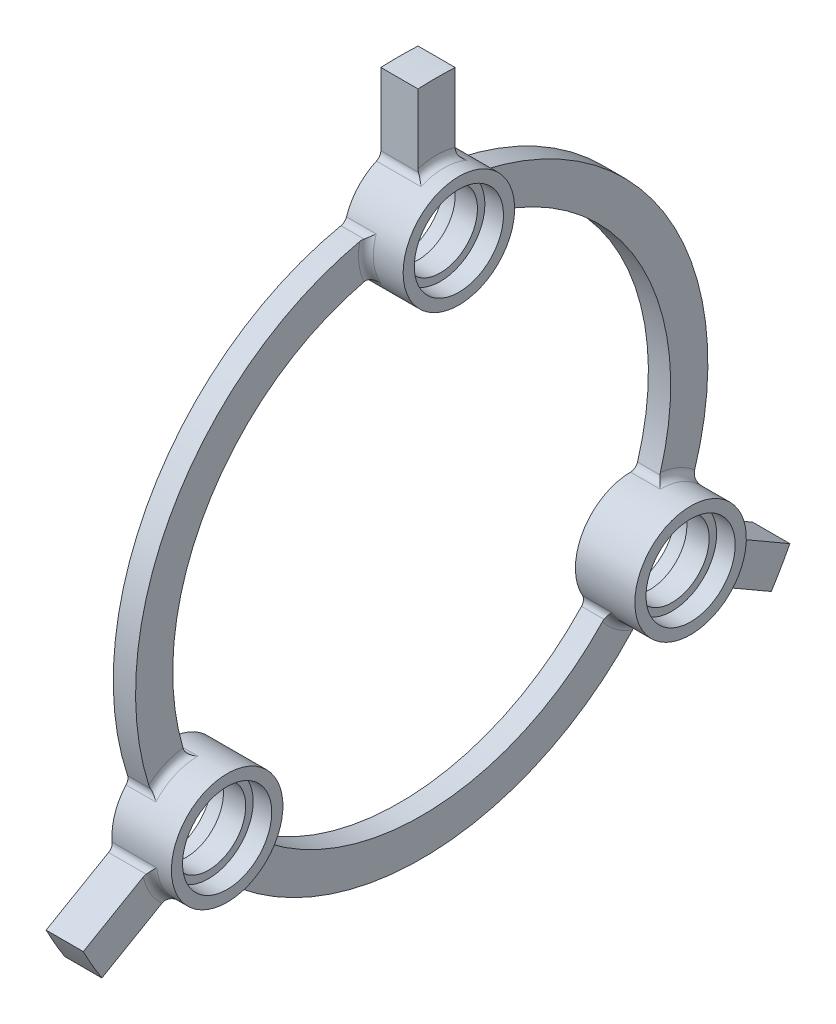
SolidWorks part; units mm, degrees
ref_plane "Спереди" through (0, 0, 0) normal (0, 0, 1) x (1, 0, 0)
ref_plane "Сверху" through (0, 0, 0) normal (0, 1, 0) x (1, 0, 0)
ref_plane "Справа" through (0, 0, 0) normal (1, 0, 0) x (0, 0, -1)
sketch "Эскиз3" plane through (0, 0, 0) normal (1, 0, 0) x (0, 0, -1)
  circle A0 centre (0, 0) radius 36 construction
  dimension "D1" = 72
sketch "Эскиз1" plane through (0, 0, 0) normal (1, 0, 0) x (0, 0, -1)
  line L0 (38.5, 0) -> (33.5, 0) construction
  circle A3 centre (0, 0) radius 38.5
  circle A4 centre (0, 0) radius 33.5
  circle A5 centre (0, 0) radius 36 construction
  point P9 (36, 0)
  dimension "D1" = 5
extrude "Бобышка-Вытянуть1" add sketch "Эскиз1" along normal blind 3
sketch "Эскиз2" plane through (0, 0, 0) normal (-1, 0, 0) x (0, 0, 1)
  circle A0 centre (0, 36) radius 7.5
  circle A1 centre (0, 0) radius 36 construction
  dimension "D1" = 15
extrude "Бобышка-Вытянуть2" add sketch "Эскиз2" against normal blind 8
sketch "Эскиз4" plane through (0, 0, 0) normal (-1, 0, 0) x (0, 0, 1)
  circle A0 centre (0, 36) radius 5
  dimension "D1" = 10
extrude "Вырез-Вытянуть1" cut sketch "Эскиз4" against normal through all
sketch "Эскиз5" plane through (0, 0, 0) normal (-1, 0, 0) x (0, 0, 1)
  circle A0 centre (0, 36) radius 6
  dimension "D1" = 12
extrude "Вырез-Вытянуть2" cut sketch "Эскиз5" against normal blind 2.5
sketch "Эскиз6" plane through (8, 0, 0) normal (1, 0, 0) x (0, 0, -1)
  circle A0 centre (0, 36) radius 6
  dimension "D1" = 12
extrude "Вырез-Вытянуть3" cut sketch "Эскиз6" against normal blind 2.5
sketch "Эскиз7" plane through (0, 0, 0) normal (-1, 0, 0) x (0, 0, 1)
  line L0 (0, 0) -> (0, 53.5) construction
  line L1 (-2.5, 53.4416) -> (-2.5, 43.0711)
  line L2 (2.5, 53.4416) -> (2.5, 43.0711)
  circle A0 centre (0, 0) radius 53.5 construction
  arc A1 (7.2794, 37.8056) -> (-7.2794, 37.8056) centre (0, 36) ccw construction
  arc A2 (-2.5, 53.4416) -> (2.5, 53.4416) centre (0, 0) cw
  arc A3 (-2.5, 43.0711) -> (2.5, 43.0711) centre (0, 36) cw
  point P13 (0, 0)
  dimension "D1" = 107
  dimension "D2" = 5
extrude "Бобышка-Вытянуть3" add sketch "Эскиз7" against normal blind 5
fillet "Скругление1" radius 1 9 edges at (3, 35.263, 7.4637) (3, 35.263, -7.4637) (1.5, 32.8056, 6.7857) (1.5, 32.8056, -6.7857) (1.5, 37.8056, -7.2794) (1.5, 37.8056, 7.2794) (5, 43.5, 0) (2.5, 43.0711, 2.5) (2.5, 43.0711, -2.5)
pattern_circular "Круговой массив1" count 3 over 360 about axis through (0, 0, 0) along (1, 0, 0) of "Бобышка-Вытянуть2", "Вырез-Вытянуть1", "Вырез-Вытянуть2", "Вырез-Вытянуть3", "Бобышка-Вытянуть3", "Скругление1"
